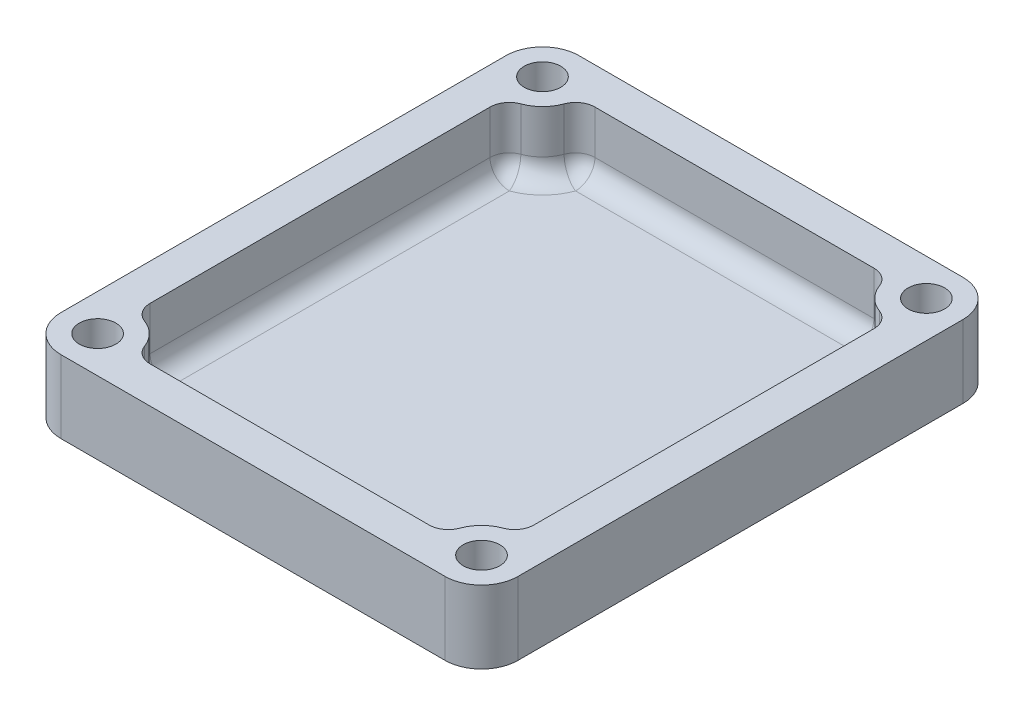
SolidWorks part; units mm, degrees
ref_plane "Front Plane" through (0, 0, 0) normal (0, 0, 1) x (1, 0, 0)
ref_plane "Top Plane" through (0, 0, 0) normal (0, 1, 0) x (1, 0, 0)
ref_plane "Right Plane" through (0, 0, 0) normal (1, 0, 0) x (0, 0, -1)
sketch "Sketch1" plane through (0, 0, 0) normal (0, 1, 0) x (1, 0, 0)
  line L1 (-31.5, -42.5) -> (31.5, -42.5)
  line L2 (-37.5, -36.5) -> (-37.5, 36.5)
  line L3 (-31.5, 42.5) -> (31.5, 42.5)
  line L4 (37.5, -36.5) -> (37.5, 36.5)
  line L5 (-37.5, -42.5) -> (37.5, 42.5) construction
  line L6 (-37.5, 42.5) -> (37.5, -42.5) construction
  arc A0 (-37.5, 36.5) -> (-31.5, 42.5) centre (-31.5, 36.5) cw
  arc A1 (-37.5, -36.5) -> (-31.5, -42.5) centre (-31.5, -36.5) ccw
  arc A2 (31.5, -42.5) -> (37.5, -36.5) centre (31.5, -36.5) ccw
  arc A3 (37.5, 36.5) -> (31.5, 42.5) centre (31.5, 36.5) ccw
  circle A4 centre (-31.5, 36.5) radius 3
  circle A5 centre (-31.5, -36.5) radius 3
  circle A6 centre (31.5, -36.5) radius 3
  circle A7 centre (31.5, 36.5) radius 3
  point P0 (0, 0)
  dimension "D1" = 6
  dimension "D4" = 6
  dimension "D2" = 75
  dimension "D3" = 85
extrude "Boss-Extrude1" add sketch "Sketch1" against normal blind 11.938
sketch "Sketch2" plane through (0, 0, 0) normal (0, 1, 0) x (1, 0, 0)
  line L1 (-22.8919, -36.5) -> (22.8919, -36.5)
  line L2 (-31.5, -27.8919) -> (-31.5, 27.8919)
  line L3 (-22.8919, 36.5) -> (22.8919, 36.5)
  line L4 (31.5, -27.8919) -> (31.5, 27.8919)
  line L5 (-31.5, -36.5) -> (31.5, 36.5) construction
  line L6 (-31.5, 36.5) -> (31.5, -36.5) construction
  arc A0 (-29.4237, 30.8707) -> (-25.8707, 34.4237) centre (-31.5, 36.5) ccw
  arc A1 (25.8707, 34.4237) -> (29.4237, 30.8707) centre (31.5, 36.5) ccw
  arc A2 (29.4237, -30.8707) -> (25.8707, -34.4237) centre (31.5, -36.5) ccw
  arc A3 (-25.8707, -34.4237) -> (-29.4237, -30.8707) centre (-31.5, -36.5) ccw
  arc A4 (-31.5, 42.5) -> (-37.5, 36.5) centre (-31.5, 36.5) ccw construction
  arc A5 (-25.8707, -34.4237) -> (-22.8919, -36.5) centre (-22.8919, -33.325) ccw
  arc A6 (29.4237, -30.8707) -> (31.5, -27.8919) centre (28.325, -27.8919) ccw
  arc A7 (25.8707, 34.4237) -> (22.8919, 36.5) centre (22.8919, 33.325) ccw
  arc A8 (-31.5, 27.8919) -> (-29.4237, 30.8707) centre (-28.325, 27.8919) cw
  arc A9 (-31.5, -27.8919) -> (-29.4237, -30.8707) centre (-28.325, -27.8919) ccw
  arc A10 (22.8919, -36.5) -> (25.8707, -34.4237) centre (22.8919, -33.325) ccw
  arc A11 (31.5, 27.8919) -> (29.4237, 30.8707) centre (28.325, 27.8919) ccw
  arc A12 (-22.8919, 36.5) -> (-25.8707, 34.4237) centre (-22.8919, 33.325) ccw
  circle A13 centre (31.5, -36.5) radius 3 construction
  circle A14 centre (-31.5, 36.5) radius 3 construction
  circle A15 centre (-31.5, -36.5) radius 3 construction
  point P0 (0, 0)
  point P34 (-28.0824, -27.2846)
  dimension "D2" = 3.175
extrude "Cut-Extrude1" cut sketch "Sketch2" against normal offset from surface 1.6002 and the other way through all up to face at (31.5, -11.938, -33.5)
fillet "Fillet1" radius 3.175 16 edges at (24.7074, -10.3378, -35.9297) (27.2574, -10.3378, -32.2574) (30.9297, -10.3378, -29.7074) (31.5, -10.3378, 0) (30.9297, -10.3378, 29.7074) (27.2574, -10.3378, 32.2574) (24.7074, -10.3378, 35.9297) (0, -10.3378, 36.5) (-24.7074, -10.3378, 35.9297) (-27.2574, -10.3378, 32.2574) (-30.9297, -10.3378, 29.7074) (-31.5, -10.3378, 0) (-30.9297, -10.3378, -29.7074) (-27.2574, -10.3378, -32.2574) (-24.7074, -10.3378, -35.9297) (0, -10.3378, -36.5)
